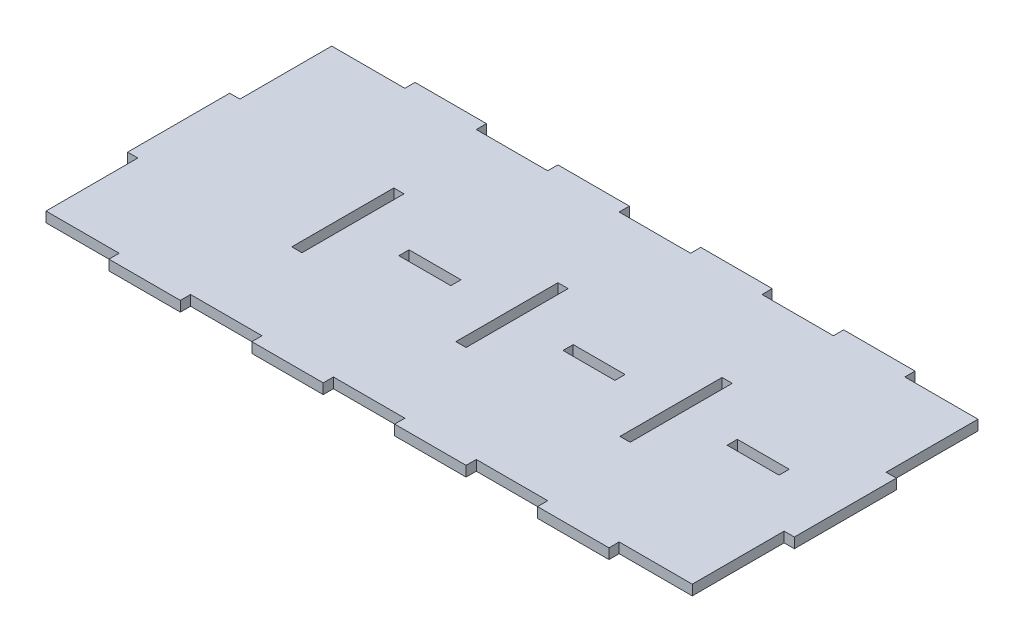
SolidWorks part; units mm, degrees
ref_plane "Front Plane" through (0, 0, 0) normal (0, 0, 1) x (1, 0, 0)
ref_plane "Top Plane" through (0, 0, 0) normal (0, 1, 0) x (1, 0, 0)
ref_plane "Right Plane" through (0, 0, 0) normal (1, 0, 0) x (0, 0, -1)
sketch "Sketch1" plane through (0, 0, 0) normal (0, 1, 0) x (1, 0, 0)
  line L0 (-98, 15) -> (-95, 15)
  line L1 (-98, -45) -> (98, -45)
  line L2 (-98, -45) -> (-98, 45)
  line L3 (-98, 45) -> (98, 45)
  line L4 (98, -45) -> (98, 45)
  line L5 (-98, -45) -> (98, 45) construction
  line L6 (-98, 45) -> (98, -45) construction
  line L7 (-95, 15) -> (-95, 45)
  line L8 (-98, -15) -> (-95, -15)
  line L9 (-95, -15) -> (-95, -45)
  line L10 (95, 45) -> (95, 15)
  line L11 (95, 15) -> (98, 15)
  line L12 (98, -15) -> (95, -15)
  line L13 (95, -15) -> (95, -45)
  line L14 (-98, -42) -> (-73.5, -42)
  line L15 (-73.5, -42) -> (-73.5, -45)
  line L16 (-73.5, -45) -> (-52.5, -45)
  line L17 (-52.5, -45) -> (-52.5, -42)
  line L18 (-52.5, -42) -> (-31.5, -42)
  line L19 (-31.5, -42) -> (-31.5, -45)
  line L20 (-31.5, -45) -> (-10.5, -45)
  line L21 (-10.5, -45) -> (-10.5, -42)
  line L22 (-10.5, -42) -> (10.5, -42)
  line L23 (10.5, -42) -> (10.5, -45)
  line L24 (10.5, -45) -> (31.5, -45)
  line L25 (31.5, -45) -> (31.5, -42)
  line L26 (31.5, -42) -> (52.5, -42)
  line L27 (52.5, -42) -> (52.5, -45)
  line L28 (52.5, -45) -> (73.5, -45)
  line L29 (73.5, -45) -> (73.5, -42)
  line L30 (73.5, -42) -> (98, -42)
  line L31 (-98, 42) -> (-73.5, 42)
  line L32 (-73.5, 42) -> (-73.5, 45)
  line L33 (-73.5, 45) -> (-52.5, 45)
  line L34 (-52.5, 45) -> (-52.5, 42)
  line L35 (-52.5, 42) -> (-31.5, 42)
  line L36 (-31.5, 42) -> (-31.5, 45)
  line L37 (-31.5, 45) -> (-10.5, 45)
  line L38 (-10.5, 45) -> (-10.5, 42)
  line L39 (-10.5, 42) -> (10.5, 42)
  line L40 (10.5, 42) -> (10.5, 45)
  line L41 (10.5, 45) -> (31.5, 45)
  line L42 (31.5, 45) -> (31.5, 42)
  line L43 (31.5, 42) -> (52.5, 42)
  line L44 (52.5, 42) -> (52.5, 45)
  line L45 (52.5, 45) -> (73.5, 45)
  line L46 (73.5, 45) -> (73.5, 42)
  line L47 (73.5, 42) -> (98, 42)
  line L49 (-49.75, -15) -> (-46.75, -15)
  line L50 (-49.75, -15) -> (-49.75, 15)
  line L51 (-49.75, 15) -> (-46.75, 15)
  line L52 (-46.75, -15) -> (-46.75, 15)
  line L53 (-49.75, -15) -> (-46.75, 15) construction
  line L54 (-49.75, 15) -> (-46.75, -15) construction
  line L55 (-1.5, -15) -> (1.5, -15)
  line L56 (-1.5, -15) -> (-1.5, 15)
  line L57 (-1.5, 15) -> (1.5, 15)
  line L58 (1.5, -15) -> (1.5, 15)
  line L59 (-1.5, -15) -> (1.5, 15) construction
  line L60 (-1.5, 15) -> (1.5, -15) construction
  line L61 (46.75, -15) -> (49.75, -15)
  line L62 (46.75, -15) -> (46.75, 15)
  line L63 (46.75, 15) -> (49.75, 15)
  line L64 (49.75, -15) -> (49.75, 15)
  line L65 (46.75, -15) -> (49.75, 15) construction
  line L66 (46.75, 15) -> (49.75, -15) construction
  line L67 (64.75, -1.5) -> (80, -1.5)
  line L68 (64.75, -1.5) -> (64.75, 1.5)
  line L69 (64.75, 1.5) -> (80, 1.5)
  line L70 (80, -1.5) -> (80, 1.5)
  line L71 (64.75, -1.5) -> (80, 1.5) construction
  line L72 (64.75, 1.5) -> (80, -1.5) construction
  line L73 (16.5, -1.5) -> (31.75, -1.5)
  line L74 (16.5, -1.5) -> (16.5, 1.5)
  line L75 (16.5, 1.5) -> (31.75, 1.5)
  line L76 (31.75, -1.5) -> (31.75, 1.5)
  line L77 (16.5, -1.5) -> (31.75, 1.5) construction
  line L78 (16.5, 1.5) -> (31.75, -1.5) construction
  line L79 (-31.75, -1.5) -> (-16.5, -1.5)
  line L80 (-31.75, -1.5) -> (-31.75, 1.5)
  line L81 (-31.75, 1.5) -> (-16.5, 1.5)
  line L82 (-16.5, -1.5) -> (-16.5, 1.5)
  line L83 (-31.75, -1.5) -> (-16.5, 1.5) construction
  line L84 (-31.75, 1.5) -> (-16.5, -1.5) construction
  point P0 (0, 0)
  point P38 (-48.25, 0)
  point P59 (0, 0)
  point P64 (48.25, 0)
  point P69 (72.375, 0)
  point P74 (24.125, 0)
  point P79 (-24.125, 0)
  dimension "D1" = 196
  dimension "D2" = 90
  dimension "D3" = 30
  dimension "D4" = 30
  dimension "D5" = 30
  dimension "D6" = 3
  dimension "D7" = 3
  dimension "D8" = 3
  dimension "D9" = 3
  dimension "D10" = 24.5
  dimension "D11" = 21
  dimension "D12" = 21
  dimension "D13" = 21
  dimension "D14" = 21
  dimension "D15" = 21
  dimension "D16" = 21
  dimension "D17" = 21
  dimension "D18" = 3
  dimension "D19" = 3
  dimension "D20" = 3
  dimension "D21" = 3
  dimension "D22" = 3
  dimension "D23" = 3
  dimension "D24" = 3
  dimension "D25" = 3
  dimension "D26" = 3
  dimension "D27" = 3
  dimension "D28" = 3
  dimension "D29" = 3
  dimension "D30" = 3
  dimension "D31" = 49.75
  dimension "D32" = 49.75
  dimension "D33" = 15.25
  dimension "D34" = 15.25
  dimension "D35" = 15.25
  dimension "D36" = 25.625
  dimension "D37" = 22.625
  dimension "D38" = 22.625
  dimension "D39" = 3
  dimension "D40" = 3
  dimension "D41" = 3
extrude "Boss-Extrude1" add sketch "Sketch1" along normal blind 3 contours L13 L12 L4 L11 L10 L3 L7 L0 L2 L8 L9 L1
